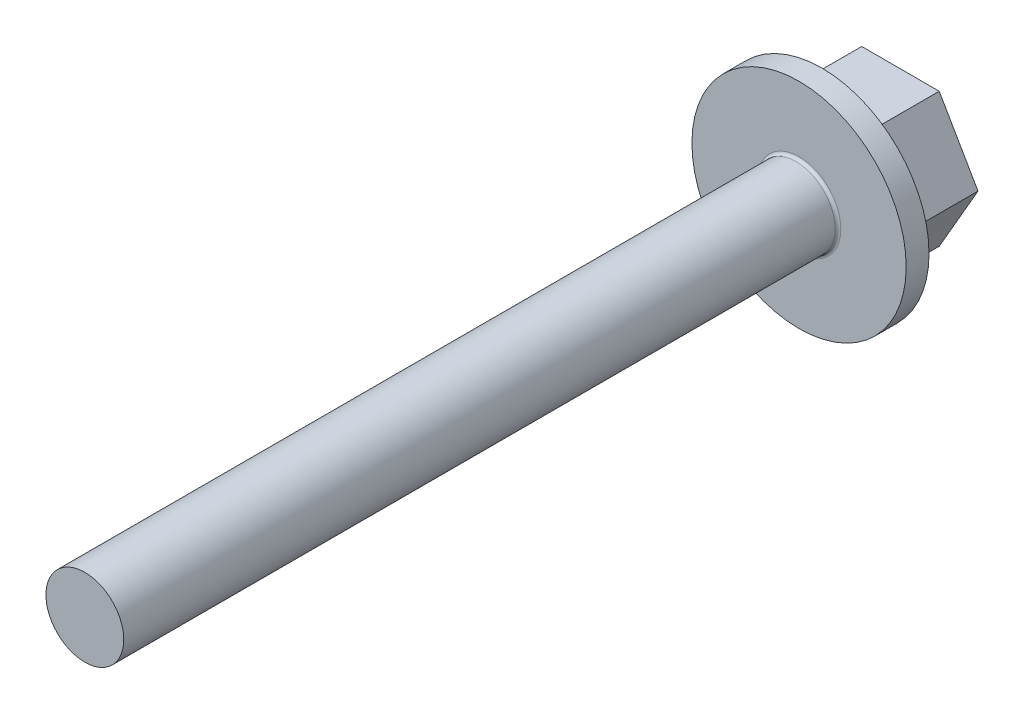
SolidWorks part; units mm, degrees
material "Ti-6Al-4VSolution treated and aged (SS)"
ref_plane "Front Plane" through (0, 0, 0) normal (0, 0, 1) x (1, 0, 0)
ref_plane "Top Plane" through (0, 0, 0) normal (0, 1, 0) x (1, 0, 0)
ref_plane "Right Plane" through (0, 0, 0) normal (1, 0, 0) x (0, 0, -1)
sketch "Sketch1" plane through (0, 0, 0) normal (0, 0, 1) x (1, 0, 0)
  line L1 (2.757, 0) -> (1.3785, 2.3876)
  line L2 (1.3785, 2.3876) -> (-1.3785, 2.3876)
  line L3 (-1.3785, 2.3876) -> (-2.757, 0)
  line L4 (-2.757, 0) -> (-1.3785, -2.3876)
  line L5 (-1.3785, -2.3876) -> (1.3785, -2.3876)
  line L6 (1.3785, -2.3876) -> (2.757, 0)
  circle A0 centre (0, 0) radius 2.3876 construction
  dimension "D1" = 4.7752
extrude "Boss-Extrude1" add sketch "Sketch1" along normal blind 2.794
sketch "Sketch2" plane through (0, 0, 2.794) normal (0, 0, 1) x (1, 0, 0)
  circle A0 centre (0, 0) radius 3.81
  dimension "D1" = 7.62
extrude "Boss-Extrude2" add sketch "Sketch2" along normal blind 0.8128
sketch "Sketch3" plane through (0, 0, 3.6068) normal (0, 0, 1) x (1, 0, 0)
  circle A0 centre (0, 0) radius 1.3843
  dimension "D1" = 2.7686
extrude "Boss-Extrude3" add sketch "Sketch3" along normal blind 25.4
fillet "Fillet1" radius 0.1016 1 edges at (1.3843, 0, 3.6068)
sketch "Sketch4" plane through (0, 0, 29.0068) normal (0, 0, 1) x (1, 0, 0)
  circle A0 centre (0, 0) radius 1.25
  dimension "D1" = 2.5
equation "\"ShankLength\"= 1.00in'Max of 1.00 in, can be sized down"
equation "\"ThreadLength\"= .073in'Min of 0.073 in, can be sized up"
